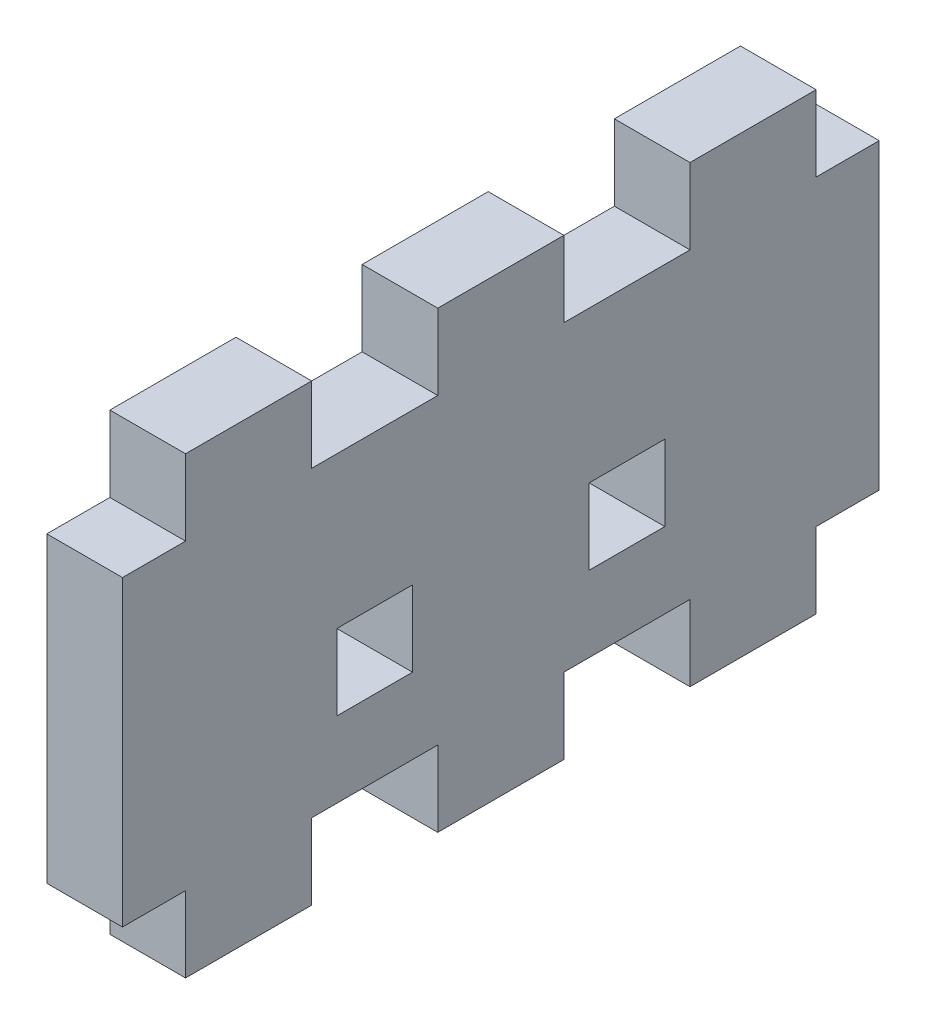
SolidWorks part; units mm, degrees
ref_plane "Front Plane" through (0, 0, 0) normal (0, 0, 1) x (1, 0, 0)
ref_plane "Top Plane" through (0, 0, 0) normal (0, 1, 0) x (1, 0, 0)
ref_plane "Right Plane" through (0, 0, 0) normal (1, 0, 0) x (0, 0, -1)
sketch "Sketch1" plane through (0, 0, 0) normal (1, 0, 0) x (0, 0, -1)
  line L1 (-15, 6) -> (15, 6)
  line L2 (-15, 6) -> (-15, -6)
  line L3 (-15, -6) -> (15, -6)
  line L4 (15, 6) -> (15, -6)
  line L5 (-15, 6) -> (15, -6) construction
  line L6 (-15, -6) -> (15, 6) construction
  point P0 (0, 0)
  dimension "D1" = 12
  dimension "D2" = 30
extrude "Boss-Extrude1" add sketch "Sketch1" along normal blind 3
sketch "Sketch3" plane through (3, 0, 0) normal (1, 0, 0) x (0, 0, -1)
  line L0 (15, 6) -> (-15, 6) construction
  line L1 (-12.5, 6) -> (-7.5, 6)
  line L2 (-12.5, 6) -> (-12.5, 9)
  line L3 (-12.5, 9) -> (-7.5, 9)
  line L4 (-7.5, 6) -> (-7.5, 9)
  line L5 (-15, 6) -> (-15, -6) construction
  line L6 (-2.5, 6) -> (2.5, 6)
  line L7 (-2.5, 6) -> (-2.5, 9)
  line L8 (-2.5, 9) -> (2.5, 9)
  line L9 (2.5, 6) -> (2.5, 9)
  line L10 (7.5, 6) -> (12.5, 6)
  line L11 (7.5, 6) -> (7.5, 9)
  line L12 (7.5, 9) -> (12.5, 9)
  line L13 (12.5, 6) -> (12.5, 9)
  line L14 (15, -6) -> (15, 6) construction
  line L15 (-18.1368, 0) -> (25.1741, 0) construction
  line L16 (12.5, -6) -> (12.5, -9)
  line L17 (7.5, -9) -> (12.5, -9)
  line L18 (7.5, -6) -> (7.5, -9)
  line L19 (7.5, -6) -> (12.5, -6)
  line L20 (2.5, -6) -> (2.5, -9)
  line L21 (-2.5, -9) -> (2.5, -9)
  line L22 (-2.5, -6) -> (-2.5, -9)
  line L23 (-2.5, -6) -> (2.5, -6)
  line L24 (-7.5, -6) -> (-7.5, -9)
  line L25 (-12.5, -9) -> (-7.5, -9)
  line L26 (-12.5, -6) -> (-12.5, -9)
  line L27 (-12.5, -6) -> (-7.5, -6)
  point P16 (-10, 9)
  point P17 (10, 9)
  point P19 (0, 9)
  dimension "D1" = 3
  dimension "D2" = 3
  dimension "D3" = 3
  dimension "D4" = 5
  dimension "D5" = 5
  dimension "D6" = 5
  dimension "D7" = 5
  dimension "D8" = 5
  dimension "D9" = 15
extrude "Boss-Extrude2" add sketch "Sketch3" against normal blind 3
sketch "Sketch4" plane through (3, 0, 0) normal (1, 0, 0) x (0, 0, -1)
  line L0 (-16.0826, -3) -> (17.0843, -3) construction
  line L1 (-15, -6) -> (-12.5, -6) construction
  line L2 (-6.5, -3) -> (-3.5, -3)
  line L3 (-6.5, -3) -> (-6.5, 0)
  line L4 (-3.5, -3) -> (-3.5, 0)
  line L5 (-6.5, 0) -> (-3.5, 0)
  line L6 (3.5, -3) -> (6.5, -3)
  line L7 (3.5, -3) -> (3.5, 0)
  line L8 (6.5, -3) -> (6.5, 0)
  line L9 (3.5, 0) -> (6.5, 0)
  line L10 (-15, 6) -> (-15, -6) construction
  line L11 (15, -6) -> (15, 6) construction
  point P4 (-5, 0)
  point P15 (5, 0)
  dimension "D1" = 3
  dimension "D2" = 3
  dimension "D3" = 3
  dimension "D4" = 3
  dimension "D5" = 3
  dimension "D6" = 10
  dimension "D7" = 10
extrude "Cut-Extrude1" cut sketch "Sketch4" against normal blind 10
